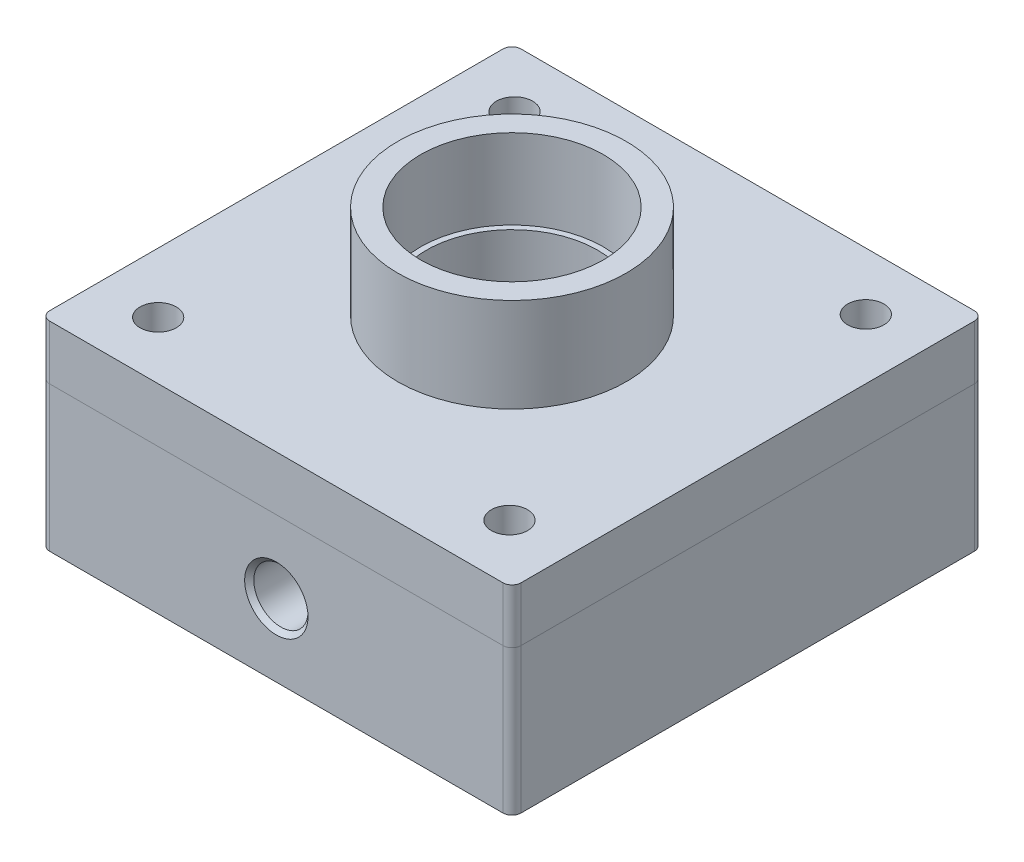
SolidWorks part; units mm, degrees
ref_plane "Front Plane" through (0, 0, 0) normal (0, 0, 1) x (1, 0, 0)
ref_plane "Top Plane" through (0, 0, 0) normal (0, 1, 0) x (1, 0, 0)
ref_plane "Right Plane" through (0, 0, 0) normal (1, 0, 0) x (0, 0, -1)
sketch "Sketch1" plane through (0, 0, 0) normal (0, 1, 0) x (1, 0, 0)
  line L1 (-82.55, 82.55) -> (82.55, 82.55)
  line L2 (-82.55, 82.55) -> (-82.55, -82.55)
  line L3 (-82.55, -82.55) -> (82.55, -82.55)
  line L4 (82.55, 82.55) -> (82.55, -82.55)
  line L5 (-82.55, 82.55) -> (82.55, -82.55) construction
  line L6 (-82.55, -82.55) -> (82.55, 82.55) construction
  point P0 (0, 0)
  dimension "D1" = 165.1
  dimension "D2" = 165.1
extrude "Boss-Extrude1" add sketch "Sketch1" along normal blind 50.8
sketch "Sketch2" plane through (0, 50.8, 0) normal (0, 1, 0) x (1, 0, 0)
  circle A0 centre (0, 0) radius 40
  dimension "D1" = 80
extrude "Boss-Extrude2" add sketch "Sketch2" along normal blind 52
sketch "Sketch3" plane through (0, 102.8, 0) normal (0, 1, 0) x (1, 0, 0)
  circle A0 centre (0, 0) radius 32
  dimension "D1" = 64
extrude "Cut-Extrude1" cut sketch "Sketch3" against normal blind 28
sketch "Sketch4" plane through (0, 74.8, 0) normal (0, 1, 0) x (1, 0, 0)
  circle A0 centre (0, 0) radius 30
  dimension "D1" = 60
extrude "Cut-Extrude2" cut sketch "Sketch4" against normal blind 22
fillet "Fillet1" radius 3.175 4 edges at (-82.55, 25.4, 82.55) (-82.55, 25.4, -82.55) (82.55, 25.4, -82.55) (82.55, 25.4, 82.55)
sketch "Sketch5" plane through (0, 0, 0) normal (0, -1, 0) x (1, 0, 0)
  circle A0 centre (0, 0) radius 20
  dimension "D1" = 40
extrude "Cut-Extrude3" cut sketch "Sketch5" against normal blind 40
sketch "Sketch6" plane through (0, 0, 0) normal (0, -1, 0) x (1, 0, 0)
  circle A0 centre (0, 0) radius 76.2
  circle A1 centre (0, 0) radius 69.85
  dimension "D1" = 152.4
  dimension "D2" = 139.7
extrude "Cut-Extrude4" cut sketch "Sketch6" against normal blind 8
sketch "Sketch7" plane through (0, 0, 82.55) normal (0, 0, 1) x (1, 0, 0)
  line L0 (-79.375, 25.4) -> (79.375, 25.4) construction
  line L1 (-79.375, 50.8) -> (-79.375, 0) construction
  line L2 (79.375, 0) -> (79.375, 50.8) construction
hole_wizard "1/2-14 NPSM Tapped Hole1" positions "Sketch8" profile "Sketch9" tap size "1/2-14 NPSM" standard "ANSI Inch"
sketch "Sketch8" plane through (0, 0, 82.55) normal (0, 0, 1) x (1, 0, 0)
  line L0 (-79.375, 25.4) -> (79.375, 25.4) construction
  point P0 (0, 25.4)
sketch "Sketch9" plane through (0, 25.4, 82.55) normal (1, 0, 0) x (0, -1, 0)
  line L0 (0, 0) -> (0, 52.9403)
  line L1 (0, 52.9403) -> (9.4869, 47.24)
  line L2 (9.4869, 47.24) -> (9.4869, 1.6002)
  line L3 (9.4869, 1.6002) -> (11.0871, 0)
  line L5 (11.0871, 0) -> (0, 0)
  line L6 (-9.4869, 1.6002) -> (-11.0871, 0) construction
  line L10 (0, 52.9403) -> (-9.4869, 47.24) construction
  line L11 (0, -6.35) -> (0, 107.95) construction
  dimension "Tap Drill Dia." = 18.9738
  dimension "Tap Drill Depth" = 47.24
  dimension "Near C'Sink Dia." = 22.1742
  dimension "Near C'Sink Angle" = 90
  dimension "Drill Angle" = 118
cosmetic thread "Hole Thread1" parameters "D1"=41.91, "D2"=20.9042
sketch "Sketch10" plane through (0, 0, 0) normal (0, -1, 0) x (1, 0, 0)
  line L0 (-79.375, 82.55) -> (79.375, 82.55) construction
  circle A0 centre (0, 50.55) radius 6.35
  dimension "D1" = 12.7
  dimension "D2" = 32
extrude "Cut-Extrude5" cut sketch "Sketch10" against normal blind 25
sketch "Sketch11" plane through (0, 0, 0) normal (0, -1, 0) x (1, 0, 0)
  line L1 (-61.5262, 62.4123) -> (61.5262, 62.4123) construction
  line L2 (-61.5262, 62.4123) -> (-61.5262, -62.4123) construction
  line L3 (-61.5262, -62.4123) -> (61.5262, -62.4123) construction
  line L4 (61.5262, 62.4123) -> (61.5262, -62.4123) construction
  line L5 (-61.5262, 62.4123) -> (61.5262, -62.4123) construction
  line L6 (-61.5262, -62.4123) -> (61.5262, 62.4123) construction
  circle A0 centre (0, 0) radius 87.64 construction
  circle A1 centre (-61.5262, 62.4123) radius 6.35
  circle A2 centre (61.5262, 62.4123) radius 6.35
  circle A3 centre (-61.5262, -62.4123) radius 6.35
  circle A4 centre (61.5262, -62.4123) radius 6.35
  dimension "D1" = 175.28
  dimension "D2" = 12.7
  dimension "D3" = 12.7
  dimension "D4" = 12.7
  dimension "D5" = 12.7
extrude "Cut-Extrude6" cut sketch "Sketch11" against normal through all
sketch "Sketch12" plane through (0, 50.8, 0) normal (0, 1, 0) x (1, 0, 0)
  line L4 (-82.55, 79.375) -> (-82.55, -79.375)
  line L5 (-79.375, -82.55) -> (79.375, -82.55)
  line L6 (82.55, -79.375) -> (82.55, 79.375)
  line L7 (79.375, 82.55) -> (-79.375, 82.55)
  line L8 (-82.55, 79.375) -> (-82.55, -79.375)
  line L9 (-79.375, -82.55) -> (79.375, -82.55)
  line L10 (82.55, -79.375) -> (82.55, 79.375)
  line L11 (79.375, 82.55) -> (-79.375, 82.55)
  circle A0 centre (61.5262, 62.4123) radius 6.35 construction
  circle A1 centre (61.5262, 62.4123) radius 6.35
  circle A2 centre (0, 0) radius 40 construction
  circle A3 centre (61.5262, -62.4123) radius 6.35 construction
  arc A4 (-82.55, -79.375) -> (-79.375, -82.55) centre (-79.375, -79.375) ccw
  arc A5 (79.375, -82.55) -> (82.55, -79.375) centre (79.375, -79.375) ccw
  arc A6 (82.55, 79.375) -> (79.375, 82.55) centre (79.375, 79.375) ccw
  arc A7 (-79.375, 82.55) -> (-82.55, 79.375) centre (-79.375, 79.375) ccw
  arc A8 (-82.55, -79.375) -> (-79.375, -82.55) centre (-79.375, -79.375) ccw
  arc A9 (79.375, -82.55) -> (82.55, -79.375) centre (79.375, -79.375) ccw
  arc A10 (82.55, 79.375) -> (79.375, 82.55) centre (79.375, 79.375) ccw
  arc A11 (-79.375, 82.55) -> (-82.55, 79.375) centre (-79.375, 79.375) ccw
  circle A12 centre (-61.5262, -62.4123) radius 6.35 construction
  circle A13 centre (-61.5262, 62.4123) radius 6.35 construction
  circle A14 centre (0, 0) radius 40
  circle A15 centre (61.5262, -62.4123) radius 6.35
  circle A16 centre (-61.5262, -62.4123) radius 6.35
  circle A17 centre (-61.5262, 62.4123) radius 6.35
  dimension "D1" = 0
extrude "Boss-Extrude4" add sketch "Sketch12" along normal blind 19.05 separate body
